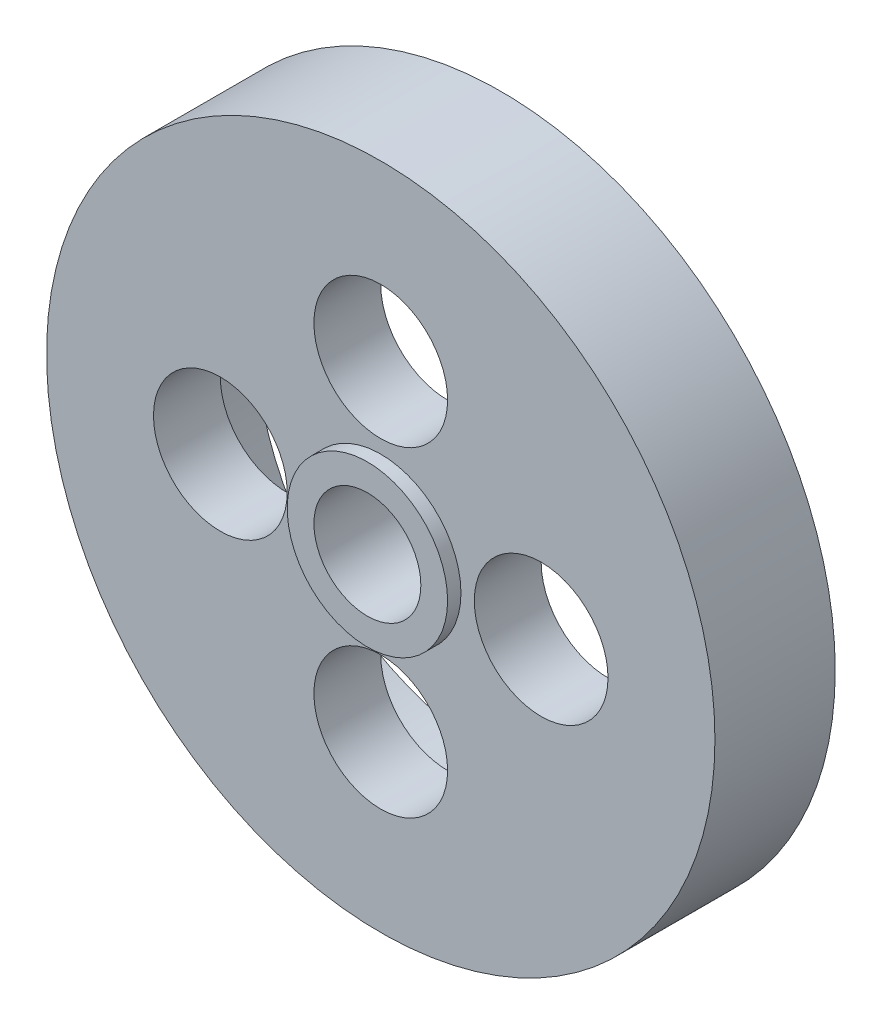
SolidWorks part; units mm, degrees
ref_plane "Ön Düzlem" through (0, 0, 0) normal (0, 0, 1) x (1, 0, 0)
ref_plane "Üst Düzlem" through (0, 0, 0) normal (0, 1, 0) x (1, 0, 0)
ref_plane "Sağ Düzlem" through (0, 0, 0) normal (1, 0, 0) x (0, 0, -1)
sketch "Sketch1" plane through (0, 0, 0) normal (0, 0, 1) x (1, 0, 0)
  circle A0 centre (0, 0) radius 25
  circle A1 centre (0, 0) radius 12 construction
  circle A2 centre (0, 12) radius 5
  circle A3 centre (12, 0) radius 5
  circle A4 centre (0, -12) radius 5
  circle A5 centre (-12, 0) radius 5
  circle A6 centre (0, 0) radius 4
  point P15 (0, 0)
  dimension "D1" = 4
  dimension "D2" = 10
  dimension "D5" = 24
  dimension "D6" = 50
extrude "Boss-Extrude1" add sketch "Sketch1" along normal blind 9
sketch "Sketch2" plane through (0, 0, 0) normal (0, 0, -1) x (-1, 0, 0)
  circle A0 centre (0, 0) radius 18
extrude "Cut-Extrude1" cut sketch "Sketch2" against normal blind 4
sketch "Sketch3" plane through (0, 0, 9) normal (0, 0, 1) x (1, 0, 0)
  circle A0 centre (0, 0) radius 6
  circle A1 centre (0, 0) radius 4 construction
  circle A2 centre (0, 0) radius 4
extrude "Boss-Extrude2" add sketch "Sketch3" along normal blind 1
sketch "Sketch4" plane through (0, 0, 0) normal (0, 1, 0) x (1, 0, 0)
  line L0 (-25, 0) -> (0, -1.0915)
  line L1 (25, 0) -> (-25, 0) construction
  line L2 (0, -1.0915) -> (0, 0)
  line L3 (0, 0) -> (-25, 0)
  line L4 (0, -9) -> (0, 0) construction
  point P5 (0, -1.0915)
  dimension "D1" = 2.5
revolve "Cut-Revolve2" cut sketch "Sketch4" angle 360 about L2
scale "Scale1" scale about centroid uniform scaling yes scale factor 1.5
